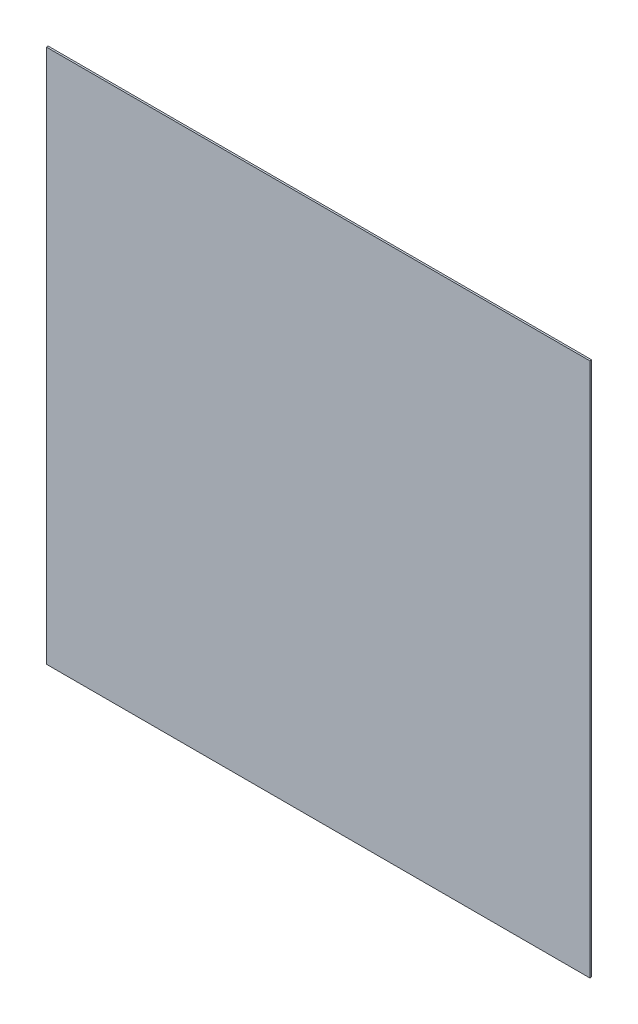
SolidWorks part; units mm, degrees
ref_plane "Спереди" through (0, 0, 0) normal (0, 0, 1) x (1, 0, 0)
ref_plane "Сверху" through (0, 0, 0) normal (0, 1, 0) x (1, 0, 0)
ref_plane "Справа" through (0, 0, 0) normal (1, 0, 0) x (0, 0, -1)
sketch "Эскиз1" plane through (0, 0, 0) normal (0, 0, 1) x (1, 0, 0)
  line L1 (0, 0) -> (600, 0)
  line L2 (0, 0) -> (0, 590)
  line L3 (0, 590) -> (600, 590)
  line L4 (600, 0) -> (600, 590)
  dimension "D1" = 590
  dimension "D2" = 600
extrude "Бобышка-Вытянуть1" add sketch "Эскиз1" along normal blind 2
